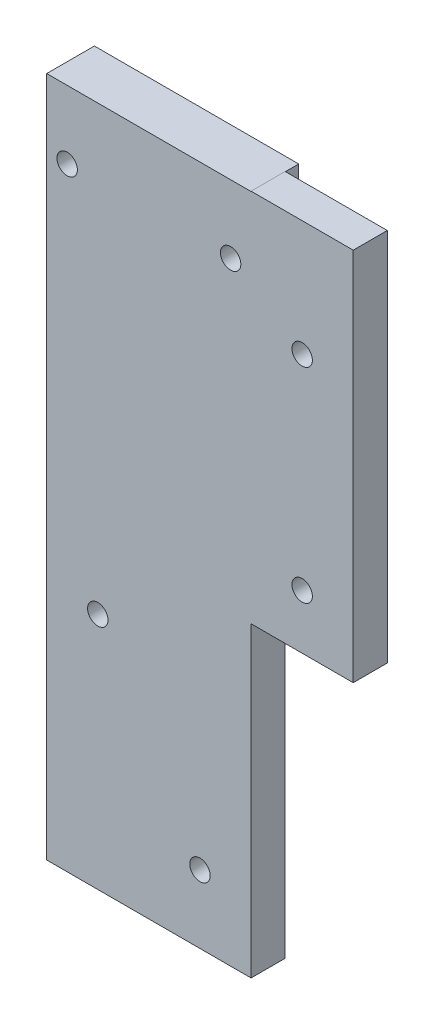
SolidWorks part; units mm, degrees
ref_plane "Alzado" through (0, 0, 0) normal (0, 0, 1) x (1, 0, 0)
ref_plane "Planta" through (0, 0, 0) normal (0, 1, 0) x (1, 0, 0)
ref_plane "Vista lateral" through (0, 0, 0) normal (1, 0, 0) x (0, 0, -1)
sketch "Croquis1" plane through (0, 0, 0) normal (0, 0, 1) x (1, 0, 0)
  line L0 (65.454, -1015) -> (65.454, -1005)
  line L1 (65.454, -1005) -> (95.454, -1015) construction
  line L2 (65.454, -1005) -> (95.454, -1005)
  line L3 (95.454, -1005) -> (95.454, -1015)
  line L4 (95.454, -1015) -> (95.454, -1105)
  line L5 (95.454, -1105) -> (65.454, -1105)
  line L6 (65.454, -1105) -> (65.454, -1015)
extrude "Saliente-Extruir1" add sketch "Croquis1" along normal blind 5 from offset 2
sketch "Croquis2" plane through (0, 0, 2) normal (0, 0, -1) x (-1, 0, 0)
  line L0 (-95.454, -1005) -> (-65.454, -1005)
  line L1 (-95.454, -1005) -> (-65.454, -1005) construction
  line L2 (-95.454, -1105) -> (-95.454, -1005) construction
  line L3 (-65.454, -1005) -> (-65.454, -1105) construction
  line L4 (-95.454, -1005) -> (-95.454, -1030)
  line L5 (-95.454, -1030) -> (-65.454, -1030)
  line L6 (-65.454, -1030) -> (-65.454, -1005)
extrude "Saliente-Extruir2" add sketch "Croquis2" along normal blind 2
sketch "Croquis3" plane through (0, 0, 2) normal (0, 0, -1) x (-1, 0, 0)
  circle A0 centre (-72.954, -1070) radius 1.5
  circle A1 centre (-87.954, -1095) radius 1.5
extrude "Cortar-Extruir1" cut sketch "Croquis3" against normal blind 10
sketch "Croquis4" plane through (0, 0, 0) normal (0, 0, -1) x (-1, 0, 0)
  circle A0 centre (-92.454, -1015) radius 1.5
  circle A1 centre (-68.454, -1015) radius 1.5
extrude "Cortar-Extruir2" cut sketch "Croquis4" against normal blind 10
sketch "Croquis5" plane through (65.454, 0, 0) normal (-1, 0, 0) x (0, 0, 1)
  line L0 (7, -1005) -> (7, -1105) construction
  line L1 (7, -1005) -> (0, -1005)
  line L2 (7, -1005) -> (7, -1030)
  line L3 (7, -1030) -> (0, -1030)
  line L4 (0, -1005) -> (0, -1030)
  line L5 (0, -1030) -> (0, -1005) construction
sketch "Croquis6" plane through (95.454, 0, 0) normal (1, 0, 0) x (0, 0, -1)
  line L6 (-2, -1105) -> (-2, -1030) construction
  line L7 (-7, -1004.9561) -> (-2, -1004.9561)
  line L8 (-7, -1004.9561) -> (-7, -1059.9561)
  line L9 (-7, -1059.9561) -> (-2, -1059.9561)
  line L10 (-2, -1004.9561) -> (-2, -1059.9561)
  dimension "D1" = 55
extrude "Saliente-Extruir3" add sketch "Croquis6" along normal blind 15
sketch "Croquis7" plane through (0, 0, 7) normal (0, 0, 1) x (1, 0, 0)
  line L0 (95.454, -1059.9561) -> (110.454, -1059.9561) construction
  line L1 (95.454, -1105) -> (95.454, -1059.9561) construction
  line L2 (110.454, -1059.9561) -> (95.454, -1059.9561) construction
  line L3 (110.454, -1059.9561) -> (102.954, -1059.9561) construction
  line L4 (102.954, -1059.9561) -> (102.954, -1051.9561) construction
  line L5 (102.954, -1051.9561) -> (102.954, -1021.9561) construction
  circle A0 centre (102.954, -1051.9561) radius 1.5
  circle A1 centre (102.954, -1021.9561) radius 1.5
  dimension "D2" = 3
  dimension "D4" = 3
  dimension "D1" = 8
  dimension "D3" = 30
extrude "Cortar-Extruir3" cut sketch "Croquis7" against normal blind 20
